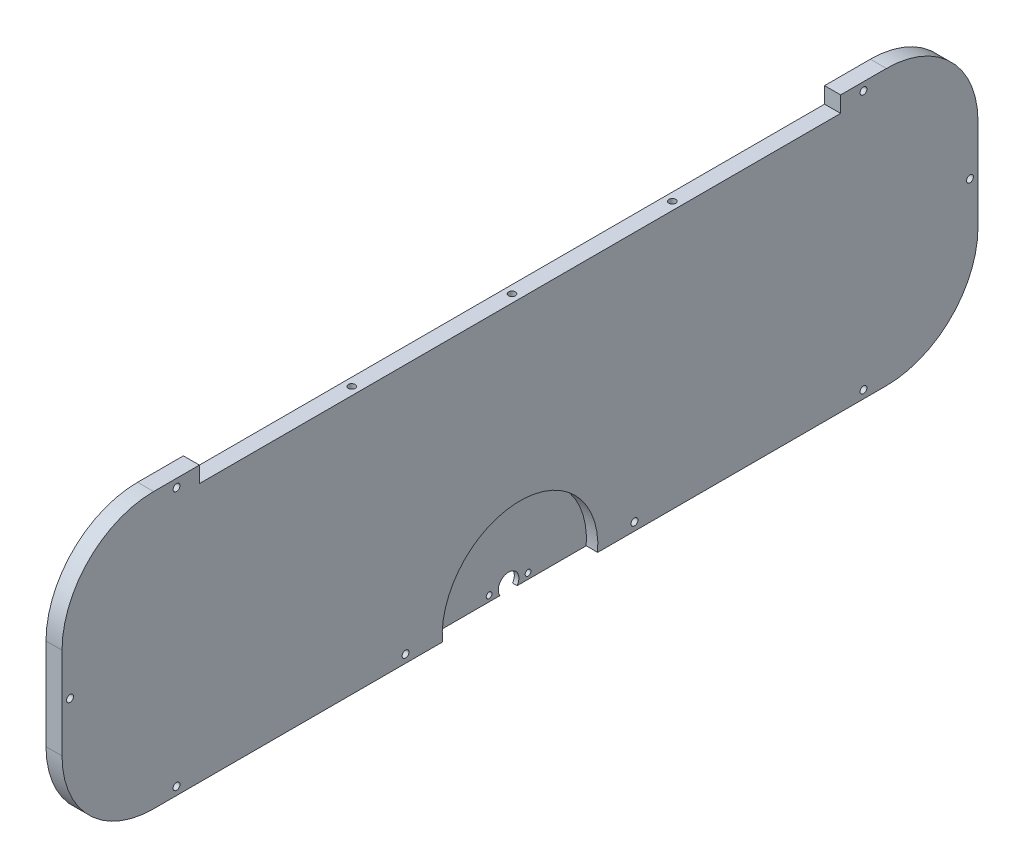
SolidWorks part; units mm, degrees
material "6061-T6 (SS)"
ref_plane "Front Plane" through (0, 0, 0) normal (0, 0, 1) x (1, 0, 0)
ref_plane "Top Plane" through (0, 0, 0) normal (0, 1, 0) x (1, 0, 0)
ref_plane "Right Plane" through (0, 0, 0) normal (1, 0, 0) x (0, 0, -1)
sketch "Sketch1" plane through (0, 0, 0) normal (1, 0, 0) x (0, 0, -1)
  line L0 (200, 0) -> (-200, 0) construction
  line L1 (0, 60) -> (0, -60) construction
  line L2 (160, 0) -> (-160, 0)
  line L3 (-200, 0) -> (-200, 120) construction
  line L4 (-200, 40) -> (-200, 80)
  line L5 (-200, 60) -> (200, 60) construction
  line L6 (0, 60) -> (0, 120) construction
  line L7 (-205.1007, 60) -> (205.1007, 60) construction
  line L8 (160, 120) -> (-160, 120)
  line L9 (200, 0) -> (200, 120) construction
  line L10 (-200, 0) -> (200, 0) construction
  line L11 (200, 40) -> (200, 80)
  arc A0 (-160, 0) -> (-200, 40) centre (-160, 40) cw
  arc A1 (-160, 120) -> (-200, 80) centre (-160, 80) ccw
  arc A2 (160, 120) -> (200, 80) centre (160, 80) cw
  arc A3 (160, 0) -> (200, 40) centre (160, 40) ccw
  point P27 (0, 0)
  dimension "D1" = 400
  dimension "D2" = 120
  dimension "D3" = 120
  dimension "D4" = 40
  dimension "D5" = 20
  dimension "D6" = 400
extrude "Boss-Extrude1" add sketch "Sketch1" along normal blind 7
sketch "Sketch2" plane through (7, 0, 0) normal (1, 0, 0) x (0, 0, -1)
  line L0 (-140, 120) -> (-140, 113)
  line L1 (160, 120) -> (-160, 120) construction
  line L2 (-140, 113) -> (140, 113)
  line L3 (140, 113) -> (140, 120)
  line L4 (-200, 80) -> (-200, 40) construction
  line L5 (200, 40) -> (200, 80) construction
  line L6 (-140, 120) -> (140, 120)
  line L7 (0, 120) -> (0, 0) construction
  line L10 (-160, 0) -> (160, 0) construction
  circle A0 centre (-150, 116.5) radius 1.5
  circle A1 centre (-196.5, 60) radius 1.5
  circle A2 centre (-50, 3.5) radius 1.5
  circle A3 centre (-150, 3.5) radius 1.5
  circle A4 centre (50, 3.5) radius 1.5
  circle A5 centre (150, 3.5) radius 1.5
  circle A6 centre (196.5, 60) radius 1.5
  circle A7 centre (150, 116.5) radius 1.5
  dimension "D4" = 3
  dimension "D5" = 3.5
  dimension "D6" = 3
  dimension "D7" = 3.5
  dimension "D8" = 3
  dimension "D9" = 3.5
  dimension "D10" = 50
  dimension "D11" = 3
  dimension "D12" = 100
  dimension "D1" = 7
  dimension "D2" = 60
  dimension "D3" = 60
extrude "Cut-Extrude1" cut sketch "Sketch2" against normal through all both and the other way through all
sketch "Sketch3" plane through (0, 113, 0) normal (0, 1, 0) x (1, 0, 0)
  line L0 (0, 140) -> (7, 140) construction
  line L1 (0, -140) -> (7, -140) construction
  circle A0 centre (3.5, 70) radius 1.5
  circle A1 centre (3.5, 0) radius 1.5
  circle A2 centre (3.5, -70) radius 1.5
  dimension "D1" = 3
  dimension "D3" = 3
  dimension "D4" = 3
  dimension "D5" = 70
  dimension "D2" = 70
extrude "Cut-Extrude2" cut sketch "Sketch3" against normal blind 10 and the other way through all from offset 3
sketch "Sketch4" plane through (7, 0, 0) normal (1, 0, 0) x (0, 0, -1)
  line L0 (-160, 0) -> (160, 0) construction
  circle A0 centre (-8.5, 2.5) radius 1.25
  circle A1 centre (8.5, 2.5) radius 1.25
  dimension "D1" = 2.5
  dimension "D2" = 2.5
  dimension "D4" = 17
  dimension "D5" = 2.5
  dimension "D6" = 2.5
  dimension "D3" = 8.5
extrude "Cut-Extrude3" cut sketch "Sketch4" against normal blind 10
sketch "Sketch5" plane through (7, 0, 0) normal (1, 0, 0) x (0, 0, -1)
  line L0 (14, -15) -> (-14, -15)
  line L2 (-14, -15) -> (-14, 5)
  line L4 (14, -15) -> (14, 5)
  arc A0 (14, 5) -> (-14, 5) centre (0, 5) ccw
  point P0 (0, 0)
  dimension "D2" = 28
extrude "Cut-Extrude4" cut sketch "Sketch5" against normal blind 4
sketch "Sketch6" plane through (3, 0, 0) normal (1, 0, 0) x (0, 0, -1)
  line L0 (-8.5, 2.5) -> (7.25, 2.5) construction
  circle A0 centre (0, 2.5) radius 4.5
  circle A2 centre (8.5, 2.5) radius 1.25 construction
  dimension "D1" = 9
extrude "Cut-Extrude5" cut sketch "Sketch6" against normal through all
sketch "Sketch7" plane through (7, 0, 0) normal (1, 0, 0) x (0, 0, -1)
  circle A0 centre (0, 2.5) radius 34
  dimension "D1" = 68
extrude "Cut-Extrude6" cut sketch "Sketch7" against normal blind 5
